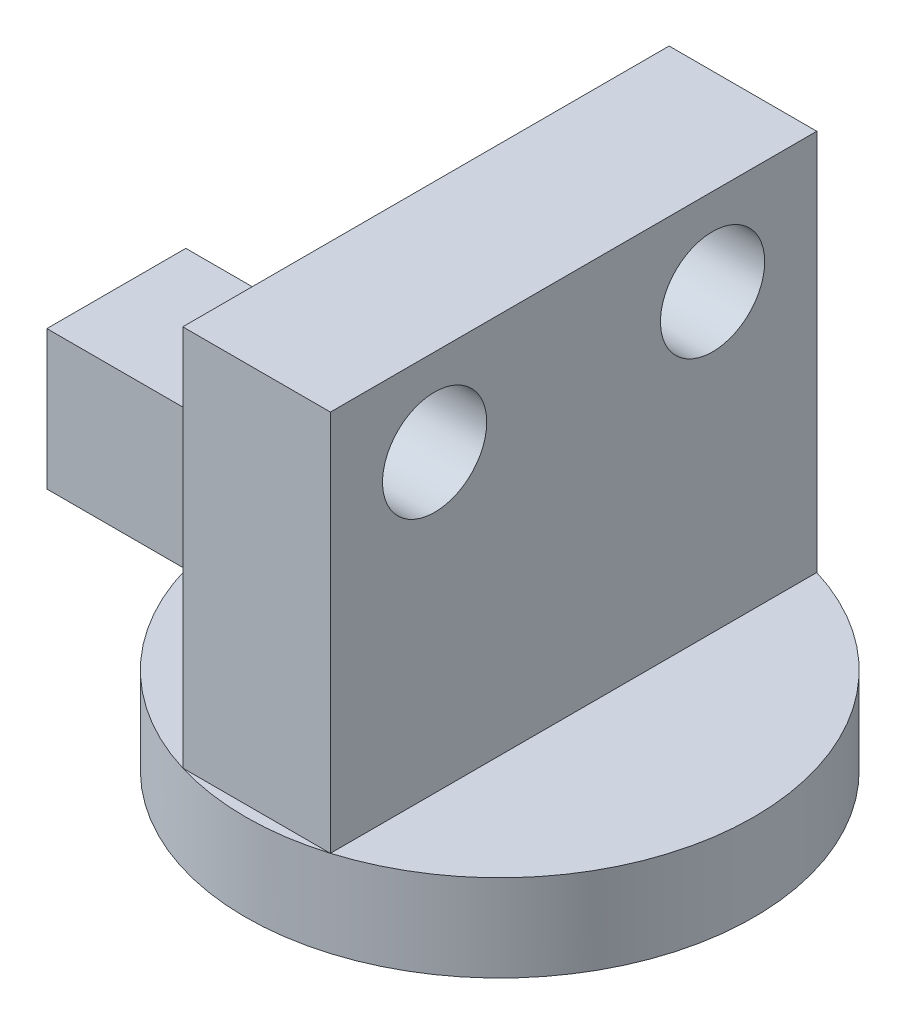
SolidWorks part; units mm, degrees
ref_plane "Front Plane" through (0, 0, 0) normal (0, 0, 1) x (1, 0, 0)
ref_plane "Top Plane" through (0, 0, 0) normal (0, 1, 0) x (1, 0, 0)
ref_plane "Right Plane" through (0, 0, 0) normal (1, 0, 0) x (0, 0, -1)
sketch "Sketch1" plane through (0, 0, 0) normal (1, 0, 0) x (0, 0, -1)
  line L0 (-101.6, 44.45) -> (101.6, 44.45) construction
  line L1 (-177.8, 107.95) -> (177.8, 107.95)
  line L2 (-177.8, 107.95) -> (-177.8, -107.95)
  line L3 (-177.8, -107.95) -> (177.8, -107.95)
  line L4 (177.8, 107.95) -> (177.8, -107.95)
  line L5 (-177.8, 107.95) -> (177.8, -107.95) construction
  line L6 (-177.8, -107.95) -> (177.8, 107.95) construction
  circle A0 centre (-101.6, 44.45) radius 38.1
  circle A1 centre (101.6, 44.45) radius 38.1
  circle A2 centre (-101.6, 44.45) radius 76.2 construction
  circle A3 centre (-101.6, 44.45) radius 57.15 construction
  point P0 (0, 0)
  point P10 (0, 44.45)
  dimension "D1" = 76.2
  dimension "D4" = 114.3
  dimension "D5" = 19.05
  dimension "D2" = 203.2
  dimension "D3" = 76.2
  dimension "D6" = 63.5
  dimension "D7" = 152.4
extrude "Boss-Extrude1" add sketch "Sketch1" along normal mid plane 107.95
sketch "Sketch4" plane through (0, -107.95, 0) normal (0, -1, 0) x (1, 0, 0)
  line L4 (-53.975, 177.8) -> (-53.975, -177.8)
  line L5 (-53.975, -177.8) -> (53.975, -177.8)
  line L6 (53.975, -177.8) -> (53.975, 177.8)
  line L7 (53.975, 177.8) -> (-53.975, 177.8)
  line L8 (-53.975, 177.8) -> (-53.975, -177.8)
  line L9 (-53.975, -177.8) -> (53.975, -177.8)
  line L10 (53.975, -177.8) -> (53.975, 177.8)
  line L11 (53.975, 177.8) -> (-53.975, 177.8)
  dimension "D1" = 0
extrude "Boss-Extrude4" add sketch "Sketch4" along normal blind 63.5
sketch "Sketch2" plane through (0, -171.45, 0) normal (0, -1, 0) x (1, 0, 0)
  line L0 (53.975, 177.8) -> (-53.975, 177.8) construction
  line L1 (53.975, 177.8) -> (-53.975, 177.8)
  circle A0 centre (0, 0) radius 185.8121
  line M8 (53.975, 177.8) -> (-53.975, 177.8)
  line M9 (-53.975, 177.8) -> (-53.975, -177.8)
  line M10 (-53.975, -177.8) -> (53.975, -177.8)
  line M11 (53.975, -177.8) -> (53.975, 177.8)
extrude "Boss-Extrude5" add sketch "Sketch2" along normal blind 63.5 contours A0 M9 | M11 M8 M9 M10 | A0 M11 | A0 M10 | A0 M8
sketch "Sketch3" plane through (0, -171.45, 0) normal (0, 1, 0) x (1, 0, 0)
  line L1 (-77.133, 50.8) -> (-178.733, 50.8)
  line L2 (-77.133, 50.8) -> (-77.133, -50.8)
  line L3 (-77.133, -50.8) -> (-178.733, -50.8)
  line L4 (-178.733, 50.8) -> (-178.733, -50.8)
  line L5 (-77.133, 50.8) -> (-178.733, -50.8) construction
  line L6 (-77.133, -50.8) -> (-178.733, 50.8) construction
  arc A1 (-53.975, 177.8) -> (-53.975, -177.8) centre (0, 0) ccw construction
  point P0 (-127.933, 0)
  point P5 (-259.115, 59.6224)
  point P8 (-253.9253, 78.8502)
  point P10 (-261.0543, -50.4585)
  dimension "D1" = 101.6
extrude "Boss-Extrude3" add sketch "Sketch3" along normal blind 101.6
sketch "Sketch5" plane through (-178.733, 0, 0) normal (-1, 0, 0) x (0, 0, 1)
  line L4 (-50.8, -171.45) -> (50.8, -171.45)
  line L5 (50.8, -171.45) -> (50.8, -69.85)
  line L6 (50.8, -69.85) -> (-50.8, -69.85)
  line L7 (-50.8, -69.85) -> (-50.8, -171.45)
  line L8 (-50.8, -171.45) -> (50.8, -171.45)
  line L9 (50.8, -171.45) -> (50.8, -69.85)
  line L10 (50.8, -69.85) -> (-50.8, -69.85)
  line L11 (-50.8, -69.85) -> (-50.8, -171.45)
  dimension "D1" = 0
extrude "Boss-Extrude6" add sketch "Sketch5" along normal blind 101.6
